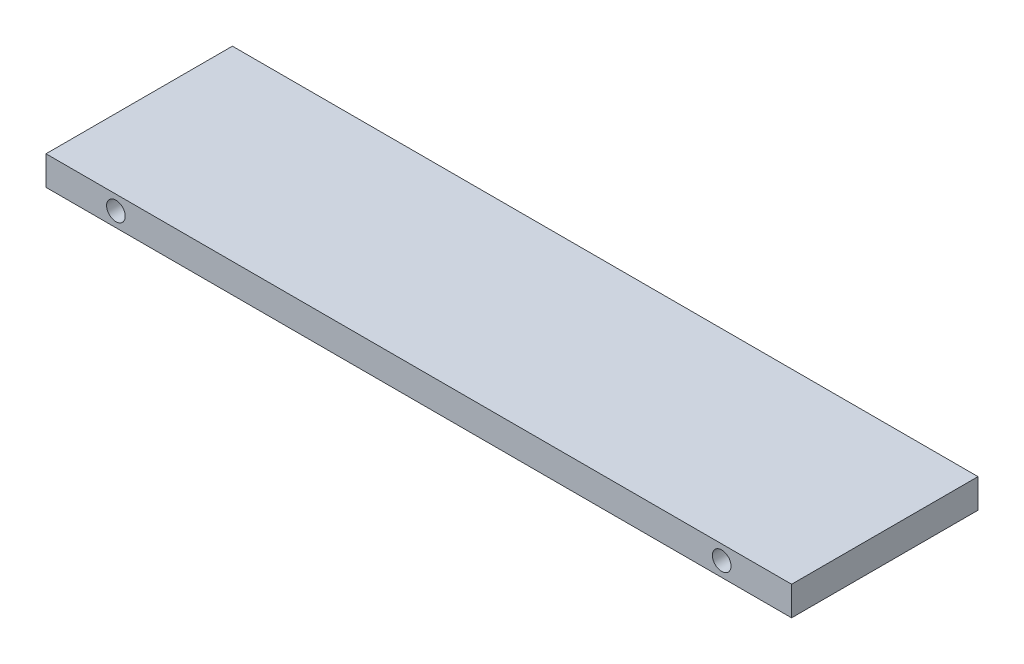
SolidWorks part; units mm, degrees
ref_plane "Front Plane" through (0, 0, 0) normal (0, 0, 1) x (1, 0, 0)
ref_plane "Top Plane" through (0, 0, 0) normal (0, 1, 0) x (1, 0, 0)
ref_plane "Right Plane" through (0, 0, 0) normal (1, 0, 0) x (0, 0, -1)
sketch "Sketch1" plane through (0, 0, 0) normal (0, 0, 1) x (1, 0, 0)
  line L0 (-32, 43.75) -> (32, 43.75)
  line L1 (32, 43.75) -> (32, 46.25)
  line L2 (32, 46.25) -> (-32, 46.25)
  line L3 (-32, 46.25) -> (-32, 43.75)
  circle A0 centre (-26, 45) radius 0.8
  circle A1 centre (26, 45) radius 0.8
extrude "Replaceable angled-rack reaction strip" add sketch "Sketch1" along normal blind 16 from offset 42
